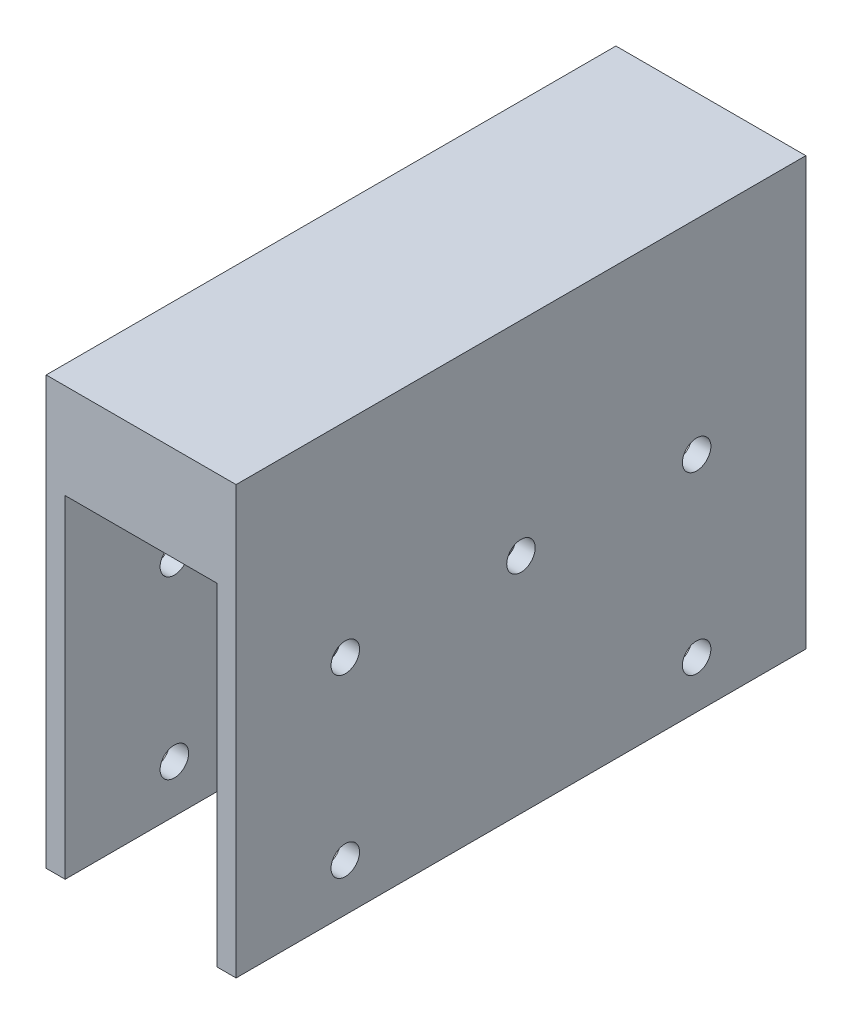
SolidWorks part; units mm, degrees
material "PETG"
ref_plane "Front Plane" through (0, 0, 0) normal (0, 0, 1) x (1, 0, 0)
ref_plane "Top Plane" through (0, 0, 0) normal (0, 1, 0) x (1, 0, 0)
ref_plane "Right Plane" through (0, 0, 0) normal (1, 0, 0) x (0, 0, -1)
sketch "Sketch1" plane through (0, 0, 0) normal (0, 0, 1) x (1, 0, 0)
  line L1 (-5, -11.25) -> (5, -11.25)
  line L2 (-5, -11.25) -> (-5, 11.25)
  line L3 (-5, 11.25) -> (5, 11.25)
  line L4 (5, -11.25) -> (5, 11.25)
  line L5 (-5, -11.25) -> (5, 11.25) construction
  line L6 (-5, 11.25) -> (5, -11.25) construction
  point P0 (0, 0)
  dimension "D1" = 10
  dimension "D2" = 22.5
extrude "Boss-Extrude1" add sketch "Sketch1" along normal blind 30
sketch "Sketch2" plane through (0, 0, 30) normal (0, 0, 1) x (1, 0, 0)
  line L0 (-5, -11.25) -> (5, -11.25) construction
  line L1 (-4, -11.25) -> (0, -11.25)
  line L2 (-4, -11.25) -> (-4, 6.25)
  line L3 (-4, 6.25) -> (0, 6.25)
  line L4 (0, -11.25) -> (0, 6.25)
  dimension "D1" = 4
  dimension "D3" = 17.5
extrude "Cut-Extrude1" cut sketch "Sketch2" against normal up to next
mirror "Mirror1" about plane through (0, 0, 0) normal (1, 0, 0) of "Cut-Extrude1"
sketch "Sketch3" plane through (5, 0, 0) normal (1, 0, 0) x (0, 0, -1)
  line L0 (-30, -11.25) -> (0, -11.25) construction
  line L1 (0, -11.25) -> (0, 11.25) construction
  circle A0 centre (-5.75, -8.75) radius 0.75
  circle A1 centre (-5.75, 0.5) radius 0.75
  dimension "D1" = 1.5
  dimension "D3" = 1.5
  dimension "D2" = 2.5
  dimension "D4" = 11.75
  dimension "D5" = 5.75
  dimension "D6" = 5.75
ref_plane "Plane1" through (0, 0, 15) normal (0, 0, 1) x (1, 0, 0)
extrude "Cut-Extrude2" cut sketch "Sketch3" against normal through all
mirror "Mirror2" about plane through (0, 0, 15) normal (0, 0, 1) of "Cut-Extrude2"
sketch "Sketch4" plane through (-5, 0, 0) normal (-1, 0, 0) x (0, 0, 1)
  line L0 (15, -5.5) -> (15, 5.5) construction
  line L1 (30, -11.25) -> (0, -11.25) construction
  circle A0 centre (15, 0.5) radius 0.75
  dimension "D1" = 1.5
  dimension "D2" = 11.75
extrude "Cut-Extrude3" cut sketch "Sketch4" against normal through all
equation "\"rail width\"= 50"
equation "\"system width\"= 125"
equation "\"system depth\"= 250"
equation "\"internal height\"= 100"
equation "\"carriage height\"= 50"
equation "\"gear radius\"= 5"
equation "\"tooth width\"= 1"
equation "\"track width\"= 10"
equation "\"D1@Sketch1\"=\"track width\""
equation "\"D2@Sketch1\"=\"track width\" / 2 + \"gear radius\" * 3.5"
equation "\"base length\"= 30"
equation "\"D1@Boss-Extrude1\"=\"base length\""
equation "\"D1@Sketch2\"=\"track width\" * 0.4"
equation "\"D3@Sketch2\"=\"gear radius\" * 3.5"
equation "\"D2@Sketch3\"=\"gear radius\" * 0.5"
equation "\"D4@Sketch3\"=\"gear radius\"*2.5 - 0.75"
equation "\"D6@Sketch3\"=\"gear radius\" + 0.75"
equation "\"D2@Sketch4\"=\"gear radius\"*2.5 - 0.75"
equation "\"D5@Sketch3\"=\"base length\"/2 - \"gear radius\"*2 +0.75"
